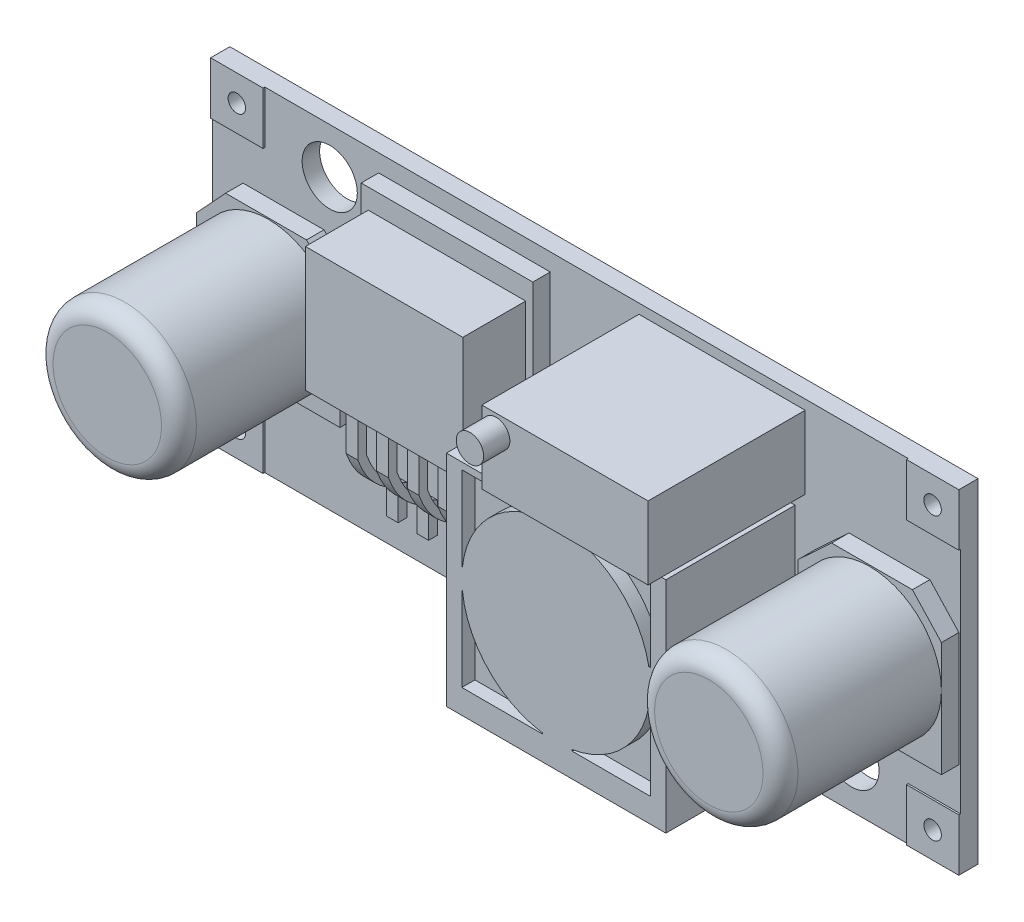
SolidWorks part; units mm, degrees
ref_plane "Front Plane" through (0, 0, 0) normal (0, 0, 1) x (1, 0, 0)
ref_plane "Top Plane" through (0, 0, 0) normal (0, 1, 0) x (1, 0, 0)
ref_plane "Right Plane" through (0, 0, 0) normal (1, 0, 0) x (0, 0, -1)
sketch "Sketch1" plane through (0, 0, 0) normal (0, 0, 1) x (1, 0, 0)
  line L1 (21.4264, -9.5637) -> (-21.4264, -9.5637)
  line L2 (21.4264, -9.5637) -> (21.4264, 9.5637)
  line L3 (21.4264, 9.5637) -> (-21.4264, 9.5637)
  line L4 (-21.4264, -9.5637) -> (-21.4264, 9.5637)
  line L5 (21.4264, -9.5637) -> (-21.4264, 9.5637) construction
  line L6 (21.4264, 9.5637) -> (-21.4264, -9.5637) construction
  circle A0 centre (-14.7064, 6.9537) radius 1.58
  circle A1 centre (15.1764, -6.774) radius 1.58
  point P0 (0, 0)
extrude "Boss-Extrude1" add sketch "Sketch1" along normal blind 1
sketch "Sketch2" plane through (0, 0, 1) normal (0, 0, 1) x (1, 0, 0)
  line L1 (-21.4264, 9.5637) -> (-18.4264, 9.5637)
  line L2 (-21.4264, 9.5637) -> (-21.4264, 6.5637)
  line L3 (-21.4264, 6.5637) -> (-18.4264, 6.5637)
  line L4 (-18.4264, 9.5637) -> (-18.4264, 6.5637)
  line L8 (-18.4264, -9.5637) -> (-18.4264, -6.5637)
  line L9 (-21.4264, -6.5637) -> (-18.4264, -6.5637)
  line L10 (-21.4264, -9.5637) -> (-21.4264, -6.5637)
  line L11 (-21.4264, -9.5637) -> (-18.4264, -9.5637)
  line L12 (21.4264, -9.5637) -> (18.4264, -9.5637)
  line L13 (21.4264, -9.5637) -> (21.4264, -6.5637)
  line L14 (21.4264, -6.5637) -> (18.4264, -6.5637)
  line L15 (18.4264, -9.5637) -> (18.4264, -6.5637)
  line L16 (18.4264, 9.5637) -> (18.4264, 6.5637)
  line L17 (21.4264, 6.5637) -> (18.4264, 6.5637)
  line L18 (21.4264, 9.5637) -> (21.4264, 6.5637)
  line L19 (21.4264, 9.5637) -> (18.4264, 9.5637)
extrude "Boss-Extrude2" add sketch "Sketch2" along normal blind 0.1
sketch "Sketch3" plane through (0, 0, 1.1) normal (0, 0, 1) x (1, 0, 0)
  circle A0 centre (-19.9264, 8.0637) radius 0.5
  circle A1 centre (-19.9264, -8.0637) radius 0.5
  circle A2 centre (19.9264, -8.0637) radius 0.5
  circle A3 centre (19.9264, 8.0637) radius 0.5
extrude "Cut-Extrude1" cut sketch "Sketch3" against normal blind 5
sketch "Sketch4" plane through (0, 0, 1) normal (0, 0, 1) x (1, 0, 0)
  line L5 (-21.3314, 2.3832) -> (-19.6699, 4.175)
  line L6 (-19.6699, 4.175) -> (-15.0378, 4.175)
  line L7 (-21.3314, -4.175) -> (-13.1214, -4.175)
  line L8 (-21.3314, -4.175) -> (-21.3314, 2.3832)
  line L9 (-19.6699, 4.175) -> (-15.0378, 4.175)
  line L10 (-13.1214, -4.175) -> (-13.1214, 2.398)
  line L11 (-21.3314, -4.175) -> (-14.0353, 3.2455) construction
  line L12 (-20.4763, 3.3054) -> (-13.1214, -4.175) construction
  line L13 (-15.0378, 4.175) -> (-13.1214, 2.398)
  line L14 (20.4763, 3.3054) -> (13.1214, -4.175) construction
  line L15 (21.3314, -4.175) -> (14.0353, 3.2455) construction
  line L16 (15.0378, 4.175) -> (13.1214, 2.398)
  line L17 (13.1214, -4.175) -> (13.1214, 2.398)
  line L18 (19.6699, 4.175) -> (15.0378, 4.175)
  line L19 (21.3314, -4.175) -> (21.3314, 2.3832)
  line L20 (21.3314, -4.175) -> (13.1214, -4.175)
  line L21 (19.6699, 4.175) -> (15.0378, 4.175)
  line L22 (21.3314, 2.3832) -> (19.6699, 4.175)
  point P13 (-17.2264, 0)
  point P28 (17.2264, 0)
extrude "Boss-Extrude3" add sketch "Sketch4" along normal blind 1 contours L13 L6 L5 L8 L7 L10 | L19 L22 L18 L16 L17 L20
sketch "Sketch5" plane through (0, 0, 2) normal (0, 0, 1) x (1, 0, 0)
  circle A0 centre (-17.2264, 0) radius 4.105
  circle A1 centre (17.2264, 0) radius 4.105
extrude "Boss-Extrude4" add sketch "Sketch5" along normal blind 9.22
fillet "Fillet1" radius 1 1 edges at (-13.1214, 0, 11.22)
fillet "Fillet2" radius 1 1 edges at (13.1214, 0, 11.22)
sketch "Sketch6" plane through (0, 0, 1) normal (0, 0, 1) x (1, 0, 0)
  line L5 (-11.9064, 8.5637) -> (-2.0764, 8.5637)
  line L6 (-11.9064, 8.5637) -> (-11.9064, -0.1863)
  line L7 (-11.9064, -0.1863) -> (-2.0764, -0.1863)
  line L8 (-2.0764, 8.5637) -> (-2.0764, -0.1863)
extrude "Boss-Extrude5" add sketch "Sketch6" along normal blind 4.6
sketch "Sketch7" plane through (0, 0, 5.6) normal (0, 0, 1) x (1, 0, 0)
  line L3 (-11.4988, 7.4182) -> (-2.4839, 7.4182)
  line L4 (-11.4988, 0.2879) -> (-2.4839, 0.2879)
  line L5 (-11.4988, 0.2879) -> (-11.4988, 7.4182)
  line L7 (-2.4839, 0.2879) -> (-2.4839, 7.4182)
  line L11 (-11.9064, -0.1863) -> (-2.0764, -0.1863)
  line L12 (-11.9064, -0.1863) -> (-11.9064, 8.5637)
  line L13 (-11.9064, 8.5637) -> (-2.0764, 8.5637)
  line L14 (-2.0764, -0.1863) -> (-2.0764, 8.5637)
  point P6 (-6.9914, 4.1887)
  point P13 (-6.9914, 4.1887)
extrude "Cut-Extrude2" cut sketch "Sketch7" against normal blind 3.6
sketch "Sketch8" plane through (0, 0.2879, 0) normal (0, -1, 0) x (-1, 0, 0)
  line L0 (9.1927, -4.7708) -> (9.1927, -1.0208)
  line L1 (10.9427, -4.7708) -> (10.2713, -4.7708)
  line L2 (10.9427, -4.7708) -> (10.9427, -1.0208)
  line L3 (10.9427, -1.0208) -> (10.2713, -1.0208)
  line L4 (10.2713, -4.7708) -> (10.2713, -1.0208)
  line L5 (9.1927, -4.7708) -> (8.5213, -4.7708)
  line L6 (8.5213, -4.7708) -> (8.5213, -1.0208)
  line L7 (9.1927, -1.0208) -> (8.5213, -1.0208)
  line L8 (7.4427, -4.7708) -> (7.4427, -1.0208)
  line L9 (7.4427, -4.7708) -> (6.7713, -4.7708)
  line L10 (6.7713, -4.7708) -> (6.7713, -1.0208)
  line L11 (7.4427, -1.0208) -> (6.7713, -1.0208)
  line L12 (5.6927, -4.7708) -> (5.6927, -1.0208)
  line L13 (5.6927, -4.7708) -> (5.0213, -4.7708)
  line L14 (5.0213, -4.7708) -> (5.0213, -1.0208)
  line L15 (5.6927, -1.0208) -> (5.0213, -1.0208)
  line L16 (3.9427, -4.7708) -> (3.9427, -1.0208)
  line L17 (3.9427, -4.7708) -> (3.2713, -4.7708)
  line L18 (3.2713, -4.7708) -> (3.2713, -1.0208)
  line L19 (3.9427, -1.0208) -> (3.2713, -1.0208)
  dimension "D1" = 5
extrude "Boss-Extrude6" add sketch "Sketch8" along normal blind 8
sketch "Sketch9" plane through (-3.2713, 0, 0) normal (1, 0, 0) x (0, 0, -1)
  line L0 (-4.7708, 0.2879) -> (-2, 0.2879) construction
  line L2 (-3.8208, 0.2879) -> (-3.8208, -3.4592)
  line L3 (-3.3208, 0.2879) -> (-2, 0.2879)
  line L4 (-3.3208, 0.2879) -> (-3.3208, -3.4592)
  line L5 (-4.7708, -7.7121) -> (-2, -7.7121)
  line L6 (-4.7708, -7.7121) -> (-4.7708, 0.2879)
  line L7 (-1.5208, -5.9544) -> (-1.5208, -7.7121)
  line L10 (-4.7708, 0.2879) -> (-3.8208, 0.2879)
  line L12 (-2, -7.7121) -> (-1.5208, -7.7121)
  line L14 (-2, -0.1863) -> (-1.0208, -0.1863)
  line L15 (-1.0208, -5.9544) -> (-1.0208, -0.1863)
  spline S0 degree 2 poles (-3.8208, -3.4592) (-3.2012, -5.2461) (-1.5208, -5.9544) knots 0 0 0 1 1 1
  spline S1 degree 2 poles (-3.3208, -3.4592) (-2.7012, -5.2461) (-1.0208, -5.9544) knots 0 0 0 1 1 1
  line M1 (-1.0208, -7.7121) -> (-1.0208, -0.1863)
  line M2 (-1.0208, -0.1863) -> (-2, -0.1863)
  line M3 (-2, -0.1863) -> (-2, 0.2879)
  line M4 (-2, 0.2879) -> (-4.7708, 0.2879)
  line M5 (-4.7708, 0.2879) -> (-4.7708, -7.7121)
  line M6 (-4.7708, -7.7121) -> (-1.0208, -7.7121)
extrude "Cut-Extrude3" cut sketch "Sketch9" against normal blind 9 contours S0 L2 L7 M4 M5 M6 | L4 S1 M1 M2 M3 M4
sketch "Sketch10" plane through (0, 0, 1) normal (0, 0, 1) x (1, 0, 0)
  line L5 (11.9464, -8.5637) -> (-0.6236, -8.5637)
  line L6 (11.9464, -8.5637) -> (11.9464, 4.0063)
  line L7 (11.9464, 4.0063) -> (-0.6236, 4.0063)
  line L8 (-0.6236, -8.5637) -> (-0.6236, 4.0063)
extrude "Boss-Extrude7" add sketch "Sketch10" along normal blind 7.4
sketch "Sketch11" plane through (0, 0, 8.4) normal (0, 0, 1) x (1, 0, 0)
  line L0 (0.2614, -1.1682) -> (0.2922, -1.2029)
  line L3 (0.2614, -2.3394) -> (0.2922, -2.3545)
  line L4 (0.2614, -7.1787) -> (4.8799, -7.1787)
  line L5 (0.2614, -7.1787) -> (0.2614, -2.3394)
  line L6 (0.2614, 3.6213) -> (4.9528, 3.6213)
  line L7 (11.0614, -7.1787) -> (11.0614, -2.7691)
  line L8 (0.2614, -7.1787) -> (11.0614, 3.6213) construction
  line L9 (0.2614, 3.6213) -> (11.0614, -7.1787) construction
  line L10 (4.9528, 3.6213) -> (4.9528, 3.5746)
  line L11 (6.2806, 3.6213) -> (6.2806, 3.5857)
  line L12 (10.9698, -0.7882) -> (11.0614, -0.7882)
  line L13 (10.9698, -2.7691) -> (11.0614, -2.7691)
  line L14 (4.8799, -7.1787) -> (4.8799, -7.1218)
  line L15 (6.582, -7.1787) -> (6.582, -7.0996)
  line L16 (6.582, -7.1787) -> (11.0614, -7.1787)
  line L17 (0.2614, -1.1682) -> (0.2614, 3.6213)
  line L18 (6.2806, 3.6213) -> (11.0614, 3.6213)
  line L19 (11.0614, -0.7882) -> (11.0614, 3.6213)
  arc A0 (6.582, -7.0996) -> (10.9698, -2.7691) centre (5.6614, -1.7787) ccw
  arc A1 (0.2922, -2.3545) -> (4.8799, -7.1218) centre (5.6614, -1.7787) ccw
  arc A2 (4.9528, 3.5746) -> (0.2922, -1.2029) centre (5.6614, -1.7787) ccw
  arc A3 (10.9698, -0.7882) -> (6.2806, 3.5857) centre (5.6614, -1.7787) ccw
  point P6 (5.6614, -1.7787)
extrude "Cut-Extrude7" cut sketch "Sketch11" against normal blind 0.75
sketch "Sketch13" plane through (0, 0, 1) normal (0, 0, 1) x (1, 0, 0)
  line L1 (12.527, 4.8371) -> (3.007, 4.8371)
  line L2 (12.527, 4.8371) -> (12.527, 9.0071)
  line L3 (12.527, 9.0071) -> (3.007, 9.0071)
  line L4 (3.007, 4.8371) -> (3.007, 9.0071)
extrude "Boss-Extrude8" add sketch "Sketch13" along normal blind 9
sketch "Sketch14" plane through (0, 0, 10) normal (0, 0, 1) x (1, 0, 0)
  circle A0 centre (3.8265, 8.0224) radius 0.7858
extrude "Boss-Extrude9" add sketch "Sketch14" along normal blind 1.5
